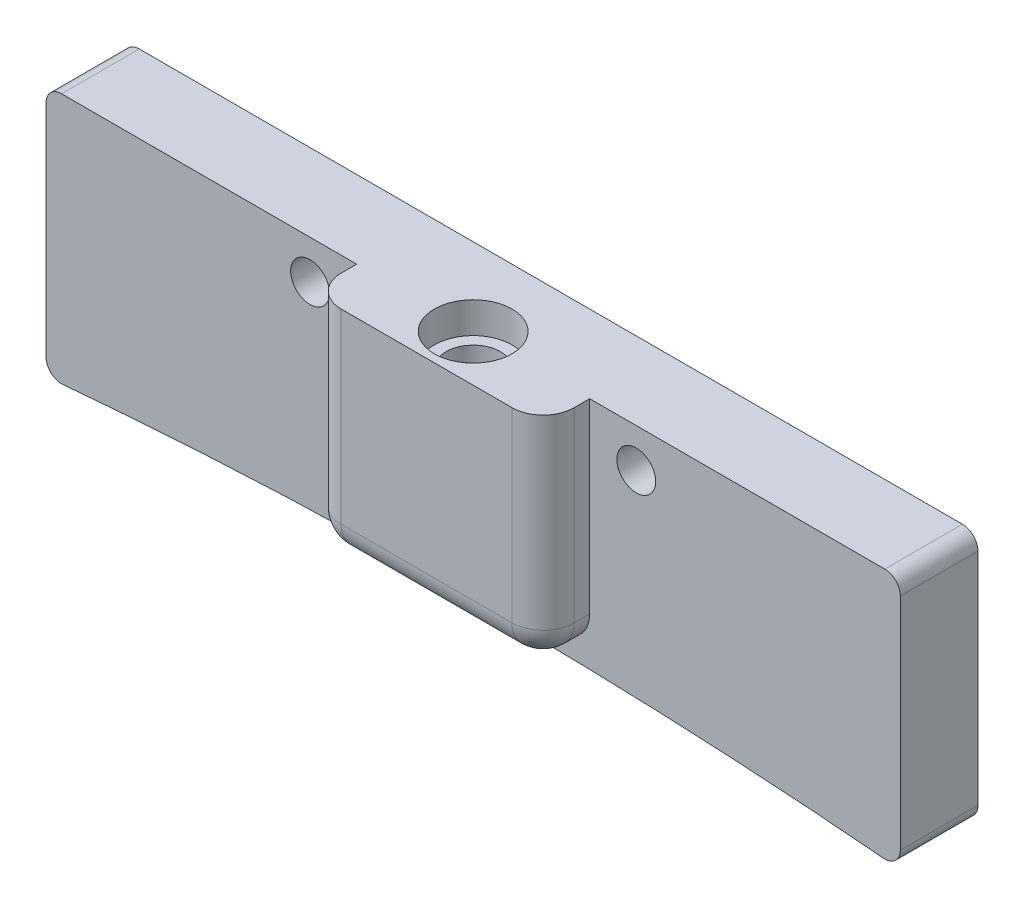
SolidWorks part; units mm, degrees
material "6061 Alloy"
ref_plane "Front Plane" through (0, 0, 0) normal (0, 0, 1) x (1, 0, 0)
ref_plane "Top Plane" through (0, 0, 0) normal (0, 1, 0) x (1, 0, 0)
ref_plane "Right Plane" through (0, 0, 0) normal (1, 0, 0) x (0, 0, -1)
ref_plane "Plane1" through (0, 0, 0) normal (0, 0, -1) x (-1, 0, 0)
sketch "Sketch1" plane through (0, 0, 0) normal (0, 0, -1) x (-1, 0, 0)
  line L0 (27.5, -16.2631) -> (27.5, 0)
  line L1 (27.5, 0) -> (-27.5, 0)
  line L2 (-27.5, 0) -> (-27.5, -16.2631)
  arc A0 (-27.5, -16.2631) -> (27.5, -16.2631) centre (0, -315) cw
extrude "Boss-Extrude1" add sketch "Sketch1" against normal blind 5
sketch "Sketch4" plane through (0, 0, 5) normal (0, 0, 1) x (1, 0, 0)
  line L0 (7.5, 0) -> (7.5, -14)
  line L1 (7.5, -14) -> (-7.5, -14)
  line L2 (-7.5, -14) -> (-7.5, 0)
  line L3 (-7.5, 0) -> (7.5, 0)
extrude "Boss-Extrude2" add sketch "Sketch4" along normal blind 3
hole_wizard "CBORE for M6 Hex Head Bolt1" positions "Sketch6" profile "Sketch5" counterbore size "M6" standard "ANSI Metric"
sketch "Sketch6" plane through (0, 0, 0) normal (0, 1, 0) x (1, 0, 0)
  point P0 (0, -5)
sketch "Sketch5" plane through (0, 0, 5) normal (1, 0, 0) x (0, 0, 1)
  line L0 (0, 0) -> (0, 11.75)
  line L1 (0, 11.75) -> (1.75, 10)
  line L2 (1.75, 10) -> (1.75, 2)
  line L3 (1.75, 2) -> (2.5, 2)
  line L4 (2.5, 2) -> (2.5, 0)
  line L5 (2.5, 0) -> (0, 0)
  line L10 (0, 11.75) -> (-1.75, 10) construction
  line L11 (0, -6.35) -> (0, 107.95) construction
  dimension "Hole Dia." = 3.5
  dimension "Hole Depth" = 10
  dimension "C'Bore Dia." = 5
  dimension "C'Bore Depth" = 2
  dimension "Drill Angle" = 90
cosmetic thread "Cosmetic Thread1" parameters "D1"=8, "D2"=8
fillet "Fillet1" radius 1 4 edges at (27.5, 0, 2.5) (-27.5, 0, 2.5) (27.5, -16.2631, 2.5) (-27.5, -16.2631, 2.5)
fillet "Fillet2" radius 2 5 edges at (7.5, -14, 6.5) (7.5, -7, 8) (-7.5, -14, 6.5) (0, -14, 8) (-7.5, -7, 8)
hole_wizard "M3x0.5 Tapped Hole1" positions "3DSketch1" profile "Sketch7" tap size "M3x0.5" standard "ANSI Metric"
sketch3d "3DSketch1"
  line L0 (-7.5, 0, 5) -> (-7.5, -12, 5) construction
  line L1 (7.5, -12, 5) -> (7.5, 0, 5) construction
  line L2 (-26.5, 0, 5) -> (-7.5, 0, 5) construction
  point P0 (-10.5, -2.5, 5)
  point P2 (10.5, -2.5, 5)
  dimension "D1" = 3
  dimension "D2" = 3
  dimension "D3" = 2.5
sketch "Sketch7" plane through (-10.5, -2.5, 5) normal (1, 0, 0) x (0, -1, 0)
  line L0 (0, 0) -> (0, 5.7511)
  line L1 (0, 5.7511) -> (1.25, 5)
  line L2 (1.25, 5) -> (1.25, 0)
  line L5 (1.25, 0) -> (0, 0)
  line L10 (0, 5.7511) -> (-1.25, 5) construction
  line L11 (0, -6.35) -> (0, 107.95) construction
  dimension "Tap Drill Dia." = 2.5
  dimension "Tap Drill Depth" = 5
  dimension "Drill Angle" = 118
